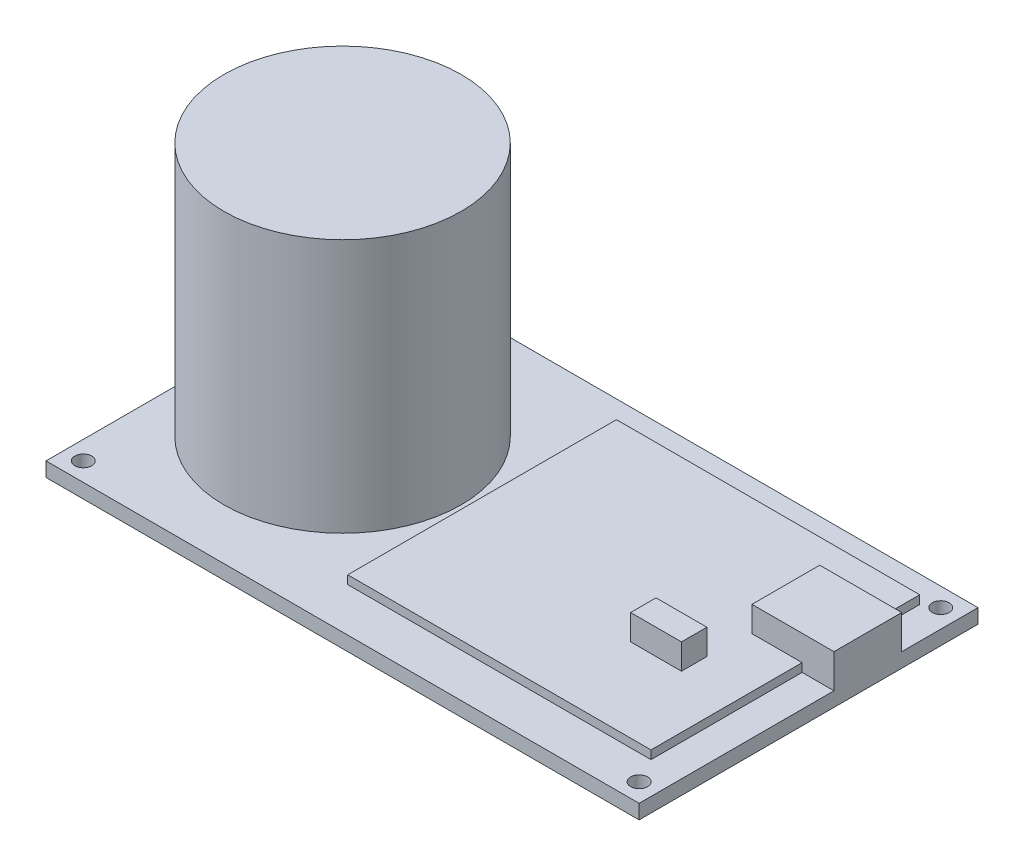
SolidWorks part; units mm, degrees
ref_plane "Front Plane" through (0, 0, 0) normal (0, 0, 1) x (1, 0, 0)
ref_plane "Top Plane" through (0, 0, 0) normal (0, 1, 0) x (1, 0, 0)
ref_plane "Right Plane" through (0, 0, 0) normal (1, 0, 0) x (0, 0, -1)
sketch "Sketch1" plane through (0, 0, 0) normal (0, 1, 0) x (1, 0, 0)
  line L1 (0, 0) -> (70, 0)
  line L2 (0, 0) -> (0, 40)
  line L3 (0, 40) -> (70, 40)
  line L4 (70, 0) -> (70, 40)
  dimension "D1" = 40
  dimension "D2" = 70
extrude "Boss-Extrude1" add sketch "Sketch1" along normal blind 1.7
sketch "Sketch2" plane through (0, 1.7, 0) normal (0, 1, 0) x (1, 0, 0)
  line L0 (70, 40) -> (0, 40) construction
  line L1 (70, 0) -> (70, 40) construction
  circle A0 centre (67.8, 37.8) radius 1
  circle A1 centre (2.2, 37.8) radius 1
  circle A2 centre (2.2, 2.2) radius 1
  circle A3 centre (67.8, 2.2) radius 1
  dimension "D1" = 2
  dimension "D2" = 2.2
  dimension "D3" = 2.2
  dimension "D4" = 2
  dimension "D5" = 2
extrude "Cut-Extrude1" cut sketch "Sketch2" against normal blind 1.7
sketch "Sketch3" plane through (0, 1.7, 0) normal (0, 1, 0) x (1, 0, 0)
  line L0 (30, 0) -> (30, 40)
  line L1 (0, 0) -> (70, 0) construction
  line L4 (70, 40) -> (0, 40) construction
  line L5 (0, 40) -> (0, 0) construction
  circle A0 centre (15, 20) radius 14
  dimension "D2" = 28
  dimension "D3" = 20
  dimension "D4" = 15
  dimension "D1" = 30
extrude "Boss-Extrude2" add sketch "Sketch3" along normal blind 30 contours A0
sketch "Sketch4" plane through (0, 1.7, 0) normal (0, 1, 0) x (1, 0, 0)
  line L0 (70, 0) -> (70, 40) construction
  line L1 (60.3215, 31) -> (70, 31)
  line L2 (60.3215, 31) -> (60.3215, 23)
  line L3 (60.3215, 23) -> (70, 23)
  line L4 (70, 31) -> (70, 23)
  line L5 (70, 40) -> (0, 40) construction
  dimension "D1" = 9
  dimension "D2" = 8
extrude "Boss-Extrude3" add sketch "Sketch4" along normal blind 4
sketch "Sketch5" plane through (0, 1.7, 0) normal (0, 1, 0) x (1, 0, 0)
  line L0 (0, 0) -> (70, 0) construction
  line L1 (54, 15) -> (60, 15)
  line L2 (54, 15) -> (54, 18)
  line L3 (54, 18) -> (60, 18)
  line L4 (60, 15) -> (60, 18)
  line L5 (70, 0) -> (70, 23) construction
  point P4 (57, 15)
  dimension "D1" = 6
  dimension "D2" = 3
  dimension "D3" = 15
  dimension "D4" = 10
extrude "Boss-Extrude4" add sketch "Sketch5" along normal blind 4
sketch "Sketch6" plane through (0, 0, 0) normal (0, -1, 0) x (1, 0, 0)
  line L0 (0, 0) -> (70, 0) construction
  line L1 (66, -4) -> (4, -4)
  line L2 (66, -4) -> (66, -36)
  line L3 (66, -36) -> (4, -36)
  line L4 (4, -4) -> (4, -36)
  line L5 (70, 0) -> (70, -40) construction
  line L6 (70, -40) -> (0, -40) construction
  line L7 (0, -40) -> (0, 0) construction
  point P10 (4, -20)
  dimension "D1" = 4
  dimension "D2" = 4
  dimension "D3" = 4
  dimension "D4" = 4
extrude "Boss-Extrude5" add sketch "Sketch6" along normal blind 1
sketch "Sketch7" plane through (0, 1.7, 0) normal (0, 1, 0) x (1, 0, 0)
  line L1 (30.4499, 5.1616) -> (66.244, 5.1616)
  line L2 (30.4499, 5.1616) -> (30.4499, 36.8793)
  line L3 (30.4499, 36.8793) -> (66.244, 36.8793)
  line L4 (66.244, 5.1616) -> (66.244, 36.8793)
extrude "Boss-Extrude6" add sketch "Sketch7" along normal blind 1
